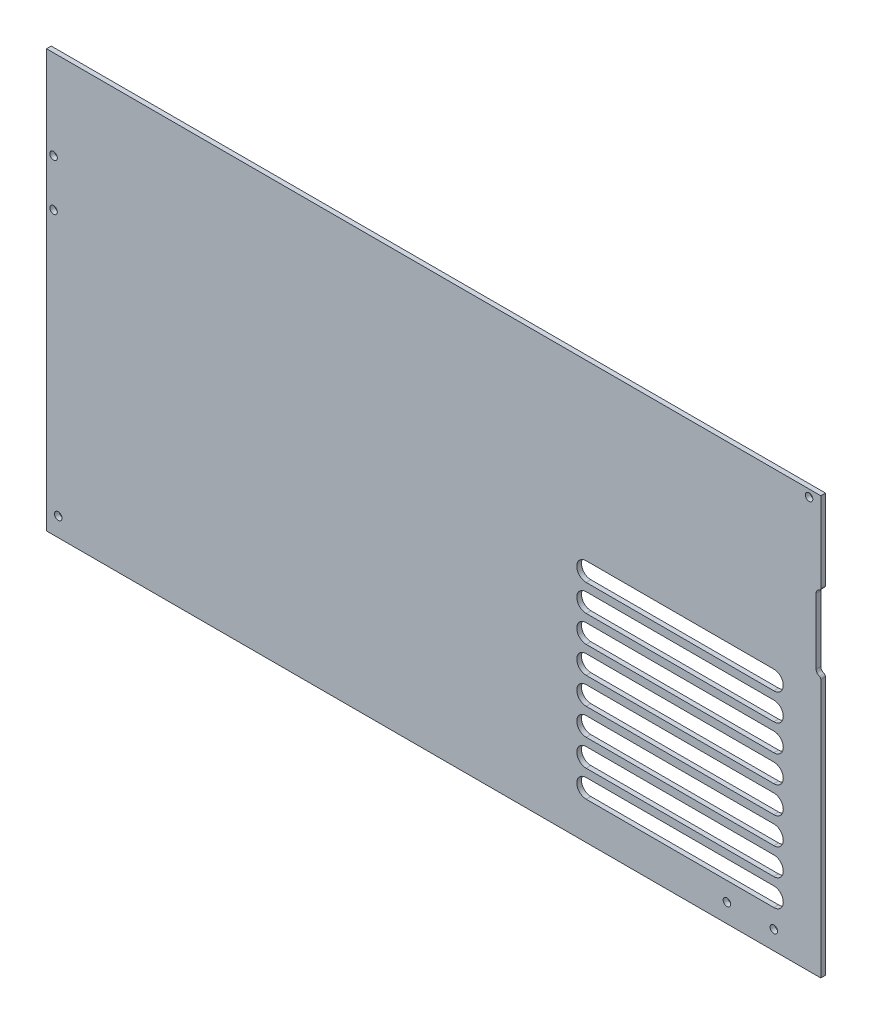
SolidWorks part; units mm, degrees
ref_plane "前视基准面" through (0, 0, 0) normal (0, 0, 1) x (1, 0, 0)
ref_plane "上视基准面" through (0, 0, 0) normal (0, 1, 0) x (1, 0, 0)
ref_plane "右视基准面" through (0, 0, 0) normal (1, 0, 0) x (0, 0, -1)
sketch "草图1" plane through (0, 0, 0) normal (0, 0, 1) x (1, 0, 0)
  line L1 (-165, -89) -> (165, -89)
  line L2 (-165, -89) -> (-165, 89)
  line L3 (-165, 89) -> (165, 89)
  line L4 (165, -89) -> (165, 89)
  line L5 (-165, -89) -> (165, 89) construction
  line L6 (-165, 89) -> (165, -89) construction
  point P0 (0, 0)
  dimension "D1" = 330
  dimension "D2" = 178
extrude "凸台-拉伸1" add sketch "草图1" along normal blind 2
sketch "草图2" plane through (0, 0, 2) normal (0, 0, 1) x (1, 0, 0)
  line L0 (65, 11) -> (145, 11) construction
  line L1 (65, 11) -> (145, 11) construction
  line L2 (65, 11) -> (65, -69) construction
  line L3 (65, -69) -> (145, -69) construction
  line L4 (145, 11) -> (145, -69) construction
  line L5 (65, 15) -> (145, 15)
  line L6 (65, 7) -> (145, 7)
  line L7 (65, -4.4286) -> (145, -4.4286)
  line L8 (65, 3.5714) -> (145, 3.5714)
  line L9 (65, -0.4286) -> (145, -0.4286) construction
  line L10 (65, -15.8571) -> (145, -15.8571)
  line L11 (65, -7.8571) -> (145, -7.8571)
  line L12 (65, -11.8571) -> (145, -11.8571) construction
  line L13 (65, -27.2857) -> (145, -27.2857)
  line L14 (65, -19.2857) -> (145, -19.2857)
  line L15 (65, -23.2857) -> (145, -23.2857) construction
  line L16 (65, -38.7143) -> (145, -38.7143)
  line L17 (65, -30.7143) -> (145, -30.7143)
  line L18 (65, -34.7143) -> (145, -34.7143) construction
  line L19 (65, -50.1429) -> (145, -50.1429)
  line L20 (65, -42.1429) -> (145, -42.1429)
  line L21 (65, -46.1429) -> (145, -46.1429) construction
  line L22 (65, -61.5714) -> (145, -61.5714)
  line L23 (65, -53.5714) -> (145, -53.5714)
  line L24 (65, -57.5714) -> (145, -57.5714) construction
  line L25 (65, -73) -> (145, -73)
  line L26 (65, -65) -> (145, -65)
  line L27 (65, -69) -> (145, -69) construction
  arc A0 (65, 15) -> (65, 7) centre (65, 11) ccw
  arc A1 (145, 7) -> (145, 15) centre (145, 11) ccw
  arc A2 (65, 3.5714) -> (65, -4.4286) centre (65, -0.4286) ccw
  arc A3 (145, -4.4286) -> (145, 3.5714) centre (145, -0.4286) ccw
  arc A4 (65, -7.8571) -> (65, -15.8571) centre (65, -11.8571) ccw
  arc A5 (145, -15.8571) -> (145, -7.8571) centre (145, -11.8571) ccw
  arc A6 (65, -19.2857) -> (65, -27.2857) centre (65, -23.2857) ccw
  arc A7 (145, -27.2857) -> (145, -19.2857) centre (145, -23.2857) ccw
  arc A8 (65, -30.7143) -> (65, -38.7143) centre (65, -34.7143) ccw
  arc A9 (145, -38.7143) -> (145, -30.7143) centre (145, -34.7143) ccw
  arc A10 (65, -42.1429) -> (65, -50.1429) centre (65, -46.1429) ccw
  arc A11 (145, -50.1429) -> (145, -42.1429) centre (145, -46.1429) ccw
  arc A12 (65, -53.5714) -> (65, -61.5714) centre (65, -57.5714) ccw
  arc A13 (145, -61.5714) -> (145, -53.5714) centre (145, -57.5714) ccw
  arc A14 (65, -65) -> (65, -73) centre (65, -69) ccw
  arc A15 (145, -73) -> (145, -65) centre (145, -69) ccw
  point P4 (105, 11)
  point P13 (105, -0.4286)
  point P20 (105, -11.8571)
  point P27 (105, -23.2857)
  point P34 (105, -34.7143)
  point P41 (105, -46.1429)
  point P48 (105, -57.5714)
  point P55 (105, -69)
  dimension "D1" = 20
  dimension "D2" = 20
  dimension "D3" = 80
  dimension "D4" = 80
  dimension "D5" = 8
  dimension "D6" = 8
extrude "切除-拉伸1" cut sketch "草图2" against normal up to next
sketch "草图3" plane through (0, 0, 2) normal (0, 0, 1) x (1, 0, 0)
  circle A0 centre (-162, 51) radius 1.6
  circle A1 centre (-162, 31) radius 1.6
  circle A2 centre (-160, -81) radius 1.6
  circle A3 centre (145, -81) radius 1.6
  circle A4 centre (125, -81) radius 1.6
  circle A5 centre (160, 86) radius 1.6
  dimension "D1" = 3.2
extrude "切除-拉伸2" cut sketch "草图3" against normal up to next
sketch "草图4" plane through (0, 0, 2) normal (0, 0, 1) x (1, 0, 0)
  line L0 (-75, 64) -> (-40, 64) construction
  line L1 (-75, 65.5) -> (-40, 65.5)
  line L2 (-75, 62.5) -> (-40, 62.5)
  line L3 (165, 89) -> (-165, 89) construction
  line L4 (-165, 89) -> (-165, -89) construction
  line L5 (-75, 59) -> (-40, 59) construction
  line L6 (-75, 60.5) -> (-40, 60.5)
  line L7 (-75, 57.5) -> (-40, 57.5)
  line L8 (-75, 54) -> (-40, 54) construction
  line L9 (-75, 55.5) -> (-40, 55.5)
  line L10 (-75, 52.5) -> (-40, 52.5)
  arc A0 (-75, 65.5) -> (-75, 62.5) centre (-75, 64) ccw
  arc A1 (-40, 62.5) -> (-40, 65.5) centre (-40, 64) ccw
  arc A2 (-75, 60.5) -> (-75, 57.5) centre (-75, 59) ccw
  arc A3 (-40, 57.5) -> (-40, 60.5) centre (-40, 59) ccw
  arc A4 (-75, 55.5) -> (-75, 52.5) centre (-75, 54) ccw
  arc A5 (-40, 52.5) -> (-40, 55.5) centre (-40, 54) ccw
  point P2 (-57.5, 64)
  point P14 (-57.5, 59)
  point P21 (-57.5, 54)
  dimension "D1" = 25
  dimension "D2" = 125
  dimension "D3" = 90
  dimension "D4" = 3
  dimension "D6" = 2
  dimension "D5" = 3
extrude "切除-拉伸3" [suppressed] cut sketch "草图4" against normal up to next and the other way through all
sketch "草图5" plane through (0, 0, 2) normal (0, 0, 1) x (1, 0, 0)
  line L0 (165, 52) -> (165, 24) construction
  line L1 (165, -89) -> (165, 89) construction
  line L2 (167, 52) -> (167, 24)
  line L3 (163, 52) -> (163, 24)
  line L4 (-165, -89) -> (165, -89) construction
  arc A0 (167, 52) -> (163, 52) centre (165, 52) ccw
  arc A1 (163, 24) -> (167, 24) centre (165, 24) ccw
  point P4 (165, 38)
  dimension "D1" = 4
  dimension "D2" = 113
  dimension "D3" = 28
extrude "切除-拉伸4" cut sketch "草图5" against normal through all
fillet "圆角1" radius 1 2 edges at (165, 22, 1) (165, 54, 1)
